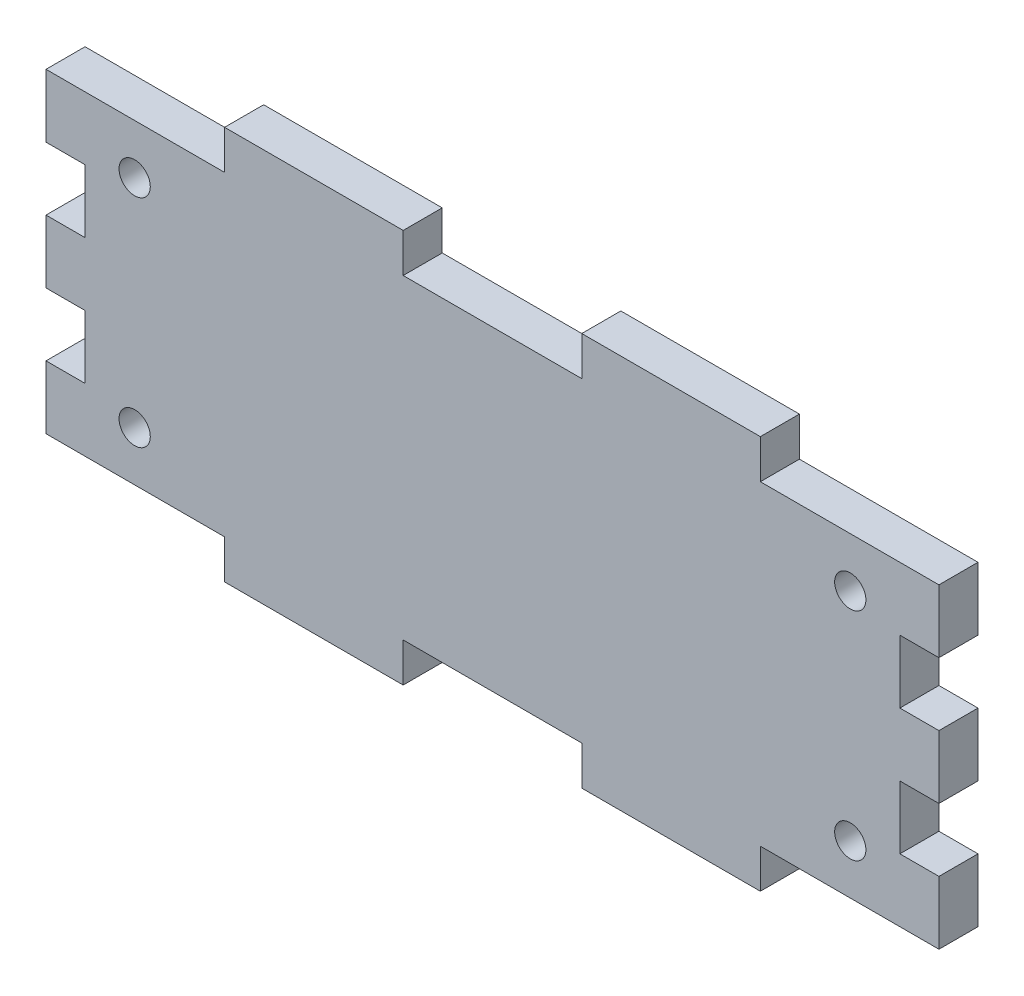
SolidWorks part; units mm, degrees
ref_plane "Front Plane" through (0, 0, 0) normal (0, 0, 1) x (1, 0, 0)
ref_plane "Top Plane" through (0, 0, 0) normal (0, 1, 0) x (1, 0, 0)
ref_plane "Right Plane" through (0, 0, 0) normal (1, 0, 0) x (0, 0, -1)
ref_plane "Plane1" through (183.8691, 57.8727, 10) normal (-1, 0, 0) x (0, 0, 1)
sketch "Sketch3" plane through (0, 0, 0) normal (0, 0, 1) x (1, 0, 0)
  line L4 (148.1491, 78.2878) -> (102.4291, 78.2878)
  line L12 (183.8691, 68.2878) -> (148.1491, 68.2878)
  line L18 (-34.7309, 78.2878) -> (-34.7309, -22.5122) construction
  line L24 (102.4291, 78.2878) -> (102.4291, 68.2878)
  line L25 (148.1491, 78.2878) -> (148.1491, 68.2878)
  line L26 (-34.7309, 35.9678) -> (-34.7309, 19.8078)
  line L27 (79.5691, 68.2878) -> (79.5691, 55.5878) construction
  line L29 (183.8691, 68.2878) -> (-24.7309, 68.2878) construction
  line L30 (102.4291, 68.2878) -> (56.7091, 68.2878)
  line L31 (193.8691, 78.2878) -> (-34.7309, 78.2878) construction
  line L33 (-34.7309, 68.2878) -> (-34.7309, 52.1278)
  line L34 (183.8691, 68.2878) -> (193.8691, 68.2878)
  line L35 (193.8691, 78.2878) -> (193.8691, -22.5122) construction
  line L36 (-24.7309, 68.2878) -> (-24.7309, -12.5122) construction
  line L37 (183.8691, -12.5122) -> (-24.7309, -12.5122) construction
  line L38 (193.8691, -22.5122) -> (-34.7309, -22.5122) construction
  line L39 (183.8691, 68.2878) -> (183.8691, -12.5122) construction
  line L40 (183.8691, 52.1278) -> (183.8691, 35.9678)
  line L41 (183.8691, 52.1278) -> (193.8691, 52.1278)
  line L42 (183.8691, 35.9678) -> (193.8691, 35.9678)
  line L43 (183.8691, 27.8878) -> (193.8691, 27.8878) construction
  line L44 (193.8691, 68.2878) -> (193.8691, 52.1278)
  line L45 (183.8691, 19.8078) -> (193.8691, 19.8078) [skipped]
  line L46 (183.8691, 3.6478) -> (193.8691, 3.6478) [skipped]
  line L47 (193.8691, 35.9678) -> (193.8691, 19.8078)
  line L48 (-24.7309, 27.8878) -> (-34.7309, 27.8878) construction
  line L49 (-24.7309, 35.9678) -> (-34.7309, 35.9678)
  line L50 (-24.7309, 52.1278) -> (-34.7309, 52.1278)
  line L51 (-24.7309, 52.1278) -> (-24.7309, 35.9678)
  line L52 (-24.7309, 68.2878) -> (-34.7309, 68.2878)
  line L53 (10.9891, 78.2878) -> (10.9891, 68.2878)
  line L54 (56.7091, 78.2878) -> (56.7091, 68.2878)
  line L55 (-24.7309, 68.2878) -> (10.9891, 68.2878)
  line L56 (10.9891, 78.2878) -> (56.7091, 78.2878)
  line L57 (148.1491, 78.2878) -> (102.4291, 78.2878)
  line L58 (183.8691, 68.2878) -> (148.1491, 68.2878)
  line L59 (102.4291, 78.2878) -> (102.4291, 68.2878)
  line L60 (148.1491, 78.2878) -> (148.1491, 68.2878)
  line L61 (183.8691, 68.2878) -> (193.8691, 68.2878)
  line L62 (183.8691, 52.1278) -> (183.8691, 35.9678)
  line L63 (183.8691, 52.1278) -> (193.8691, 52.1278)
  line L64 (183.8691, 35.9678) -> (193.8691, 35.9678)
  line L65 (183.8691, 27.8878) -> (193.8691, 27.8878) construction
  line L66 (-34.7309, 35.9678) -> (-34.7309, 19.8078)
  line L67 (-34.7309, 68.2878) -> (-34.7309, 52.1278)
  line L68 (-24.7309, 27.8878) -> (-34.7309, 27.8878) construction
  line L69 (-24.7309, 35.9678) -> (-34.7309, 35.9678)
  line L70 (-24.7309, 52.1278) -> (-34.7309, 52.1278)
  line L71 (-24.7309, 52.1278) -> (-24.7309, 35.9678)
  line L72 (-24.7309, 68.2878) -> (-34.7309, 68.2878)
  line L73 (193.8691, 68.2878) -> (193.8691, 52.1278)
  line L74 (193.8691, 35.9678) -> (193.8691, 19.8078)
  line L75 (10.9891, 78.2878) -> (10.9891, 68.2878)
  line L76 (56.7091, 78.2878) -> (56.7091, 68.2878)
  line L77 (-24.7309, 68.2878) -> (10.9891, 68.2878)
  line L78 (10.9891, 78.2878) -> (56.7091, 78.2878)
  line L79 (79.5691, -12.5122) -> (79.5691, 0.1878) construction
  line L80 (10.9891, -22.5122) -> (56.7091, -22.5122)
  line L81 (-24.7309, -12.5122) -> (10.9891, -12.5122)
  line L82 (56.7091, -22.5122) -> (56.7091, -12.5122)
  line L83 (10.9891, -22.5122) -> (10.9891, -12.5122)
  line L84 (193.8691, -12.5122) -> (193.8691, 3.6478)
  line L85 (-24.7309, -12.5122) -> (-34.7309, -12.5122)
  line L86 (-24.7309, 3.6478) -> (-24.7309, 19.8078)
  line L87 (-24.7309, 3.6478) -> (-34.7309, 3.6478)
  line L88 (-24.7309, 19.8078) -> (-34.7309, 19.8078)
  line L89 (-34.7309, -12.5122) -> (-34.7309, 3.6478)
  line L90 (183.8691, 19.8078) -> (193.8691, 19.8078)
  line L91 (183.8691, 3.6478) -> (193.8691, 3.6478)
  line L92 (183.8691, 3.6478) -> (183.8691, 19.8078)
  line L93 (183.8691, -12.5122) -> (193.8691, -12.5122)
  line L94 (148.1491, -22.5122) -> (148.1491, -12.5122)
  line L95 (102.4291, -22.5122) -> (102.4291, -12.5122)
  line L96 (183.8691, -12.5122) -> (148.1491, -12.5122)
  line L97 (148.1491, -22.5122) -> (102.4291, -22.5122)
  line L98 (10.9891, -22.5122) -> (56.7091, -22.5122)
  line L99 (-24.7309, -12.5122) -> (10.9891, -12.5122)
  line L100 (56.7091, -22.5122) -> (56.7091, -12.5122)
  line L101 (10.9891, -22.5122) -> (10.9891, -12.5122)
  line L102 (-24.7309, -12.5122) -> (-34.7309, -12.5122)
  line L103 (-24.7309, 3.6478) -> (-24.7309, 19.8078)
  line L104 (-24.7309, 3.6478) -> (-34.7309, 3.6478)
  line L105 (-24.7309, 19.8078) -> (-34.7309, 19.8078)
  line L106 (193.8691, -12.5122) -> (193.8691, 3.6478)
  line L107 (183.8691, 19.8078) -> (193.8691, 19.8078)
  line L108 (183.8691, 3.6478) -> (193.8691, 3.6478)
  line L109 (183.8691, 3.6478) -> (183.8691, 19.8078)
  line L110 (183.8691, -12.5122) -> (193.8691, -12.5122)
  line L111 (-34.7309, -12.5122) -> (-34.7309, 3.6478)
  line L112 (102.4291, -12.5122) -> (56.7091, -12.5122)
  line L113 (148.1491, -22.5122) -> (148.1491, -12.5122)
  line L114 (102.4291, -22.5122) -> (102.4291, -12.5122)
  line L115 (183.8691, -12.5122) -> (148.1491, -12.5122)
  line L116 (148.1491, -22.5122) -> (102.4291, -22.5122)
  circle A1 centre (171.1691, 55.5878) radius 4
  circle A5 centre (-12.0309, 55.5878) radius 4
  circle A6 centre (171.1691, 55.5878) radius 4
  circle A7 centre (-12.0309, 55.5878) radius 4
  circle A8 centre (-12.0309, 0.1878) radius 4
  circle A9 centre (171.1691, 0.1878) radius 4
  circle A10 centre (-12.0309, 0.1878) radius 4
  circle A11 centre (171.1691, 0.1878) radius 4
  point P10 (79.5691, 27.8878)
  dimension "D1" = 5
  dimension "D5" = 10
extrude "Boss-Extrude2" add sketch "Sketch3" along normal blind 10 contours L112 L95 L97 L94 L96 L93 L84 L91 L92 L90 L47 L42 L40 L41 L44 L34 L12 L25 L4 L24 L30 L54 L56 L53 L55 L52 L33 L50 L51 L49 L26 L88 L86 L87 L89 L85 L81 L83 L80 L82 A5 A1 A8 A9
